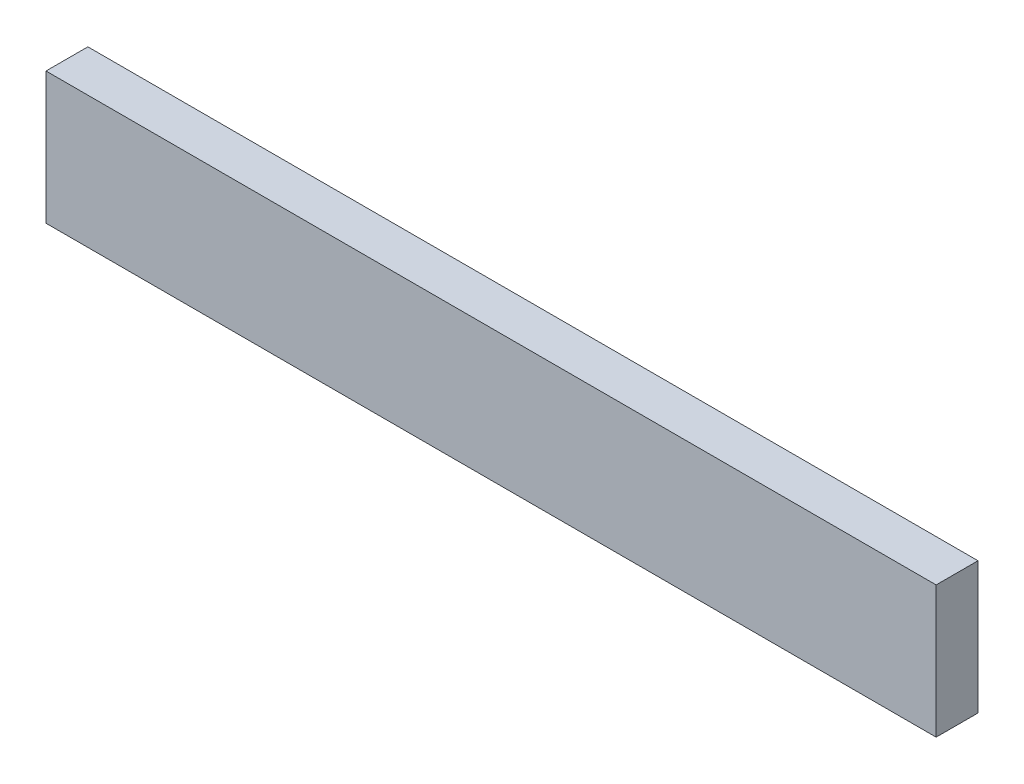
SolidWorks part; units mm, degrees
ref_plane "Front Plane" through (0, 0, 0) normal (0, 0, 1) x (1, 0, 0)
ref_plane "Top Plane" through (0, 0, 0) normal (0, 1, 0) x (1, 0, 0)
ref_plane "Right Plane" through (0, 0, 0) normal (1, 0, 0) x (0, 0, -1)
sketch "Sketch2" plane through (0, 0, 0) normal (0, 0, 1) x (1, 0, 0)
  line L1 (-135, -20) -> (135, -20)
  line L2 (-135, -20) -> (-135, 20)
  line L3 (-135, 20) -> (135, 20)
  line L4 (135, -20) -> (135, 20)
  line L5 (-135, -20) -> (135, 20) construction
  line L6 (-135, 20) -> (135, -20) construction
  point P0 (0, 0)
  dimension "D1" = 270
  dimension "D2" = 40
extrude "Boss-Extrude1" add sketch "Sketch2" along normal blind 12.7
